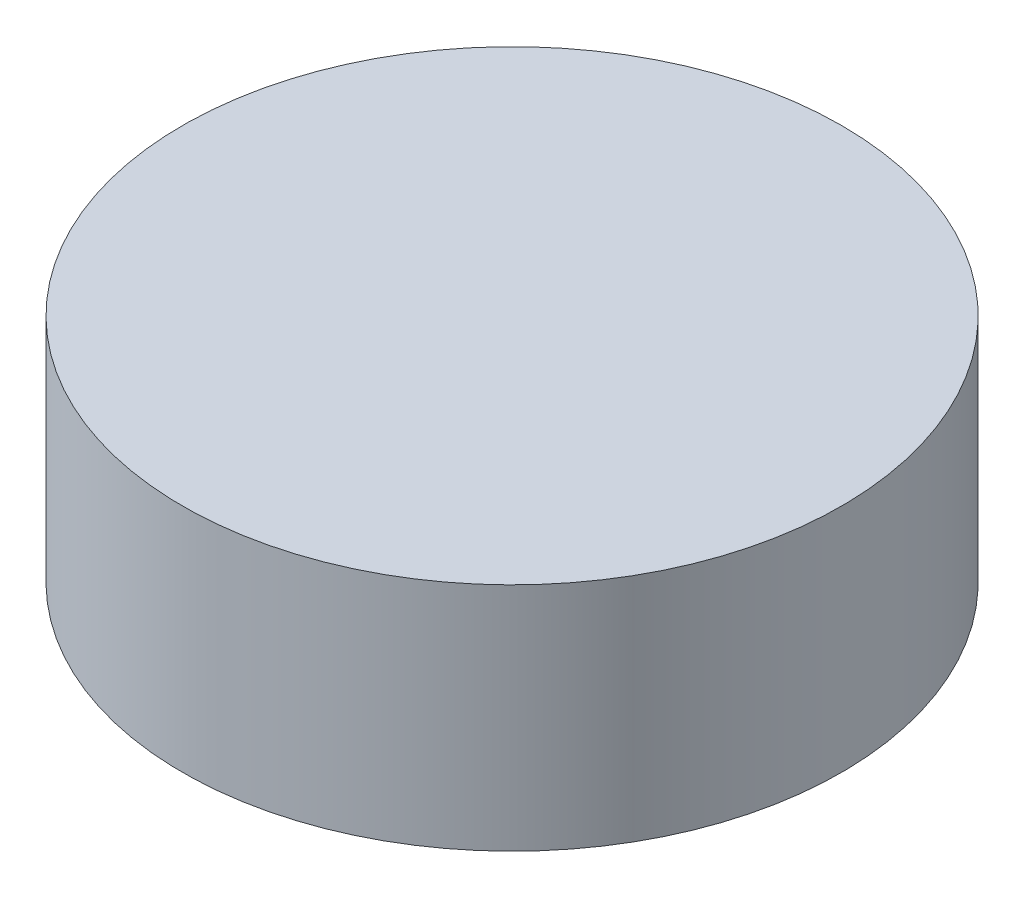
SolidWorks part; units mm, degrees
ref_plane "Alzado" through (0, 0, 0) normal (0, 0, 1) x (1, 0, 0)
ref_plane "Planta" through (0, 0, 0) normal (0, 1, 0) x (1, 0, 0)
ref_plane "Vista lateral" through (0, 0, 0) normal (1, 0, 0) x (0, 0, -1)
ref_plane "Plano_TacoPVC1" through (0, 18, 0) normal (0, 1, 0) x (1, 0, 0)
sketch "SkTacoPVC1" plane through (0, 18, 0) normal (0, 1, 0) x (1, 0, 0)
  circle A0 centre (150, 0) radius 20
extrude "TacoPVC1" add sketch "SkTacoPVC1" along normal blind 14 separate body
